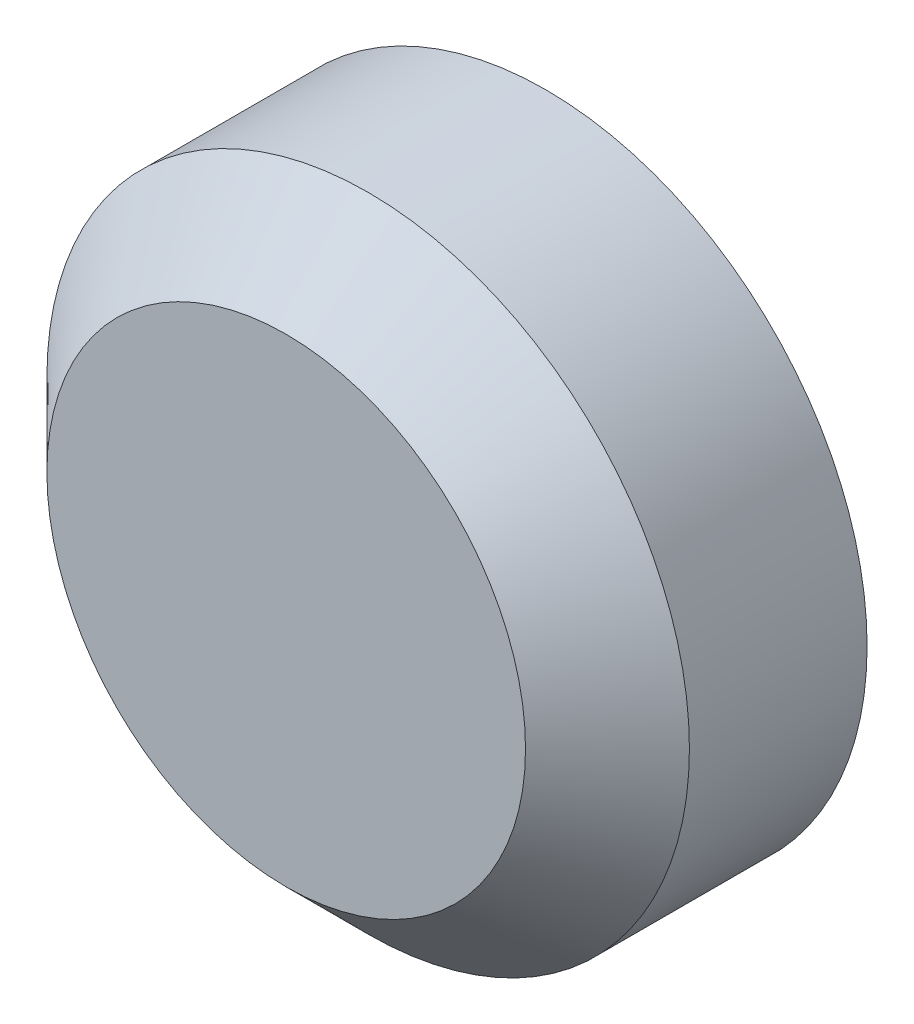
SolidWorks part; units mm, degrees
material "Delrin 2700 NC010, Low Viscosity Acetal Copolymer (SS)"
ref_plane "Front Plane" through (0, 0, 0) normal (0, 0, 1) x (1, 0, 0)
ref_plane "Top Plane" through (0, 0, 0) normal (0, 1, 0) x (1, 0, 0)
ref_plane "Right Plane" through (0, 0, 0) normal (1, 0, 0) x (0, 0, -1)
sketch "Sketch1" plane through (0, 0, 0) normal (0, 0, 1) x (1, 0, 0)
  circle A0 centre (0, 0) radius 6.223
  dimension "D1" = 12.446
extrude "Boss-Extrude1" add sketch "Sketch1" along normal blind 5.0292
chamfer "Chamfer1" distance 1.5875 angle 45 1 edges at (6.223, 0, 5.0292)
